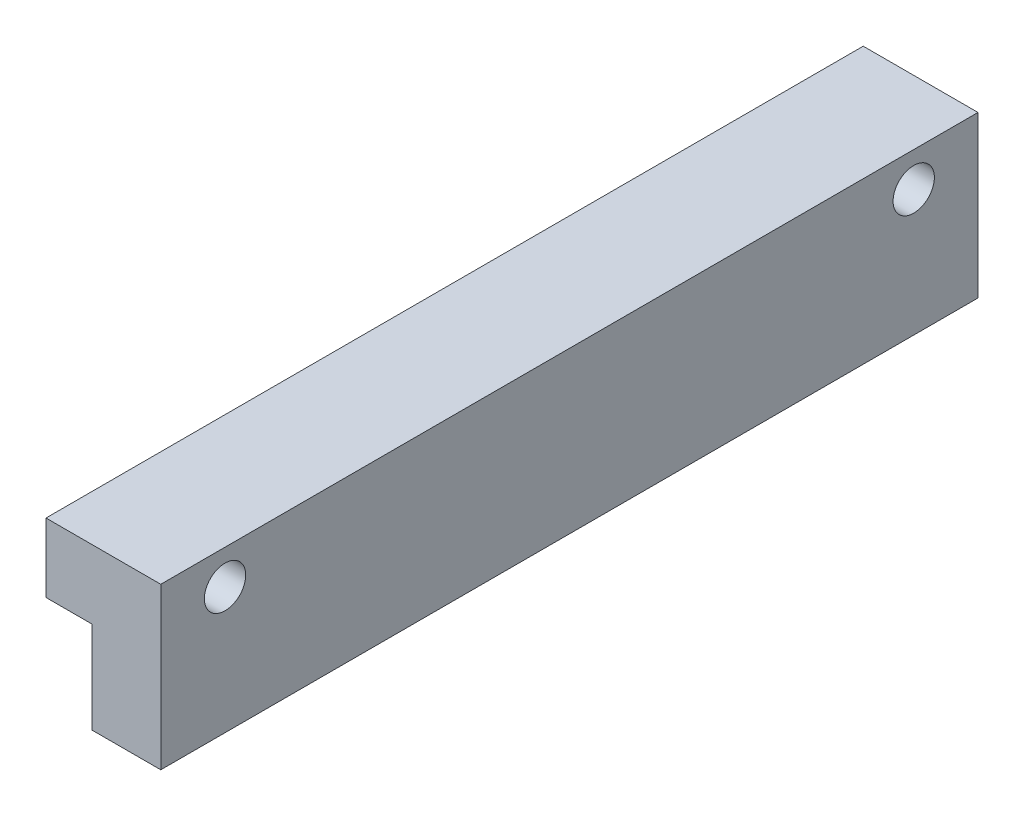
SolidWorks part; units mm, degrees
material "3.3535 (Al Mg3)"
ref_plane "Vorne" through (0, 0, 0) normal (0, 0, 1) x (1, 0, 0)
ref_plane "Oben" through (0, 0, 0) normal (0, 1, 0) x (1, 0, 0)
ref_plane "Rechts" through (0, 0, 0) normal (1, 0, 0) x (0, 0, -1)
sketch "Skizze1" plane through (0, 0, 0) normal (0, 0, 1) x (1, 0, 0)
  line L0 (0, 0) -> (15, 0)
  line L1 (15, 0) -> (15, 35)
  line L2 (15, 35) -> (-10, 35)
  line L3 (-10, 35) -> (-10, 20)
  line L4 (-10, 20) -> (0, 20)
  line L5 (0, 20) -> (0, 0)
  dimension "D1" = 20
  dimension "D2" = 15
  dimension "D3" = 15
  dimension "D4" = 25
extrude "Aufsatz-Linear austragen1" add sketch "Skizze1" along normal mid plane 178
hole_wizard "M8 Gewindebohrung1" positions "Skizze3" profile "Skizze2" tap size "M8" standard "Gabler-Normteile"
sketch "Skizze3" plane through (0, 0, 0) normal (0, -1, 0) x (-1, 0, 0)
  line L0 (-7.5, 70) -> (-7.5, -70) construction
  line L1 (0, 89) -> (-15, 89) construction
  line L2 (-15, -89) -> (-15, 89) construction
  point P0 (-7.5, -70)
  point P2 (-7.5, 70)
  point P9 (-7.5, 0)
  dimension "D1" = 19
  dimension "D2" = 7.5
sketch "Skizze2" plane through (7.5, 0, 70) normal (1, 0, 0) x (0, 0, -1)
  line L0 (0, 0) -> (0, 20.2929)
  line L1 (0, 20.2929) -> (3.4, 18.25)
  line L2 (3.4, 18.25) -> (3.4, 0)
  line L5 (3.4, 0) -> (0, 0)
  line L10 (0, 20.2929) -> (-3.4, 18.25) construction
  line L11 (0, -6.35) -> (0, 107.95) construction
  dimension "Bohrerdurchmesser" = 6.8
  dimension "Bohrungstiefe" = 18.25
  dimension "Spitzenwinkel" = 118
cosmetic thread "Bohrungsgewinde1" parameters "D1"=12, "D2"=8
cosmetic thread "Bohrungsgewinde2" parameters "D1"=12, "D2"=8
hole_wizard "Ø9.0 (9) Durchmesser Bohrung1" positions "Skizze6" profile "Skizze4" hole size "Ø9.0" standard "Gabler-Normteile" end condition through all
sketch "Skizze6" plane through (15, 0, 0) normal (1, 0, 0) x (0, 0, -1)
  line L0 (-75, 27.5) -> (75, 27.5) construction
  line L1 (-89, 35) -> (89, 35) construction
  point P0 (-75, 27.5)
  point P2 (75, 27.5)
  point P8 (0, 27.5)
  dimension "D1" = 7.5
  dimension "D2" = 150
sketch "Skizze4" plane through (15, 27.5, 75) normal (0, 1, 0) x (0, 0, -1)
  line L0 (0, 0) -> (0, 25)
  line L1 (0, 25) -> (4.5, 25)
  line L2 (4.5, 25) -> (4.5, 0)
  line L5 (4.5, 0) -> (0, 0)
  line L11 (0, -6.35) -> (0, 107.95) construction
  dimension "Bohrerdurchmesser" = 9
  dimension "Bohrungstiefe" = 25
